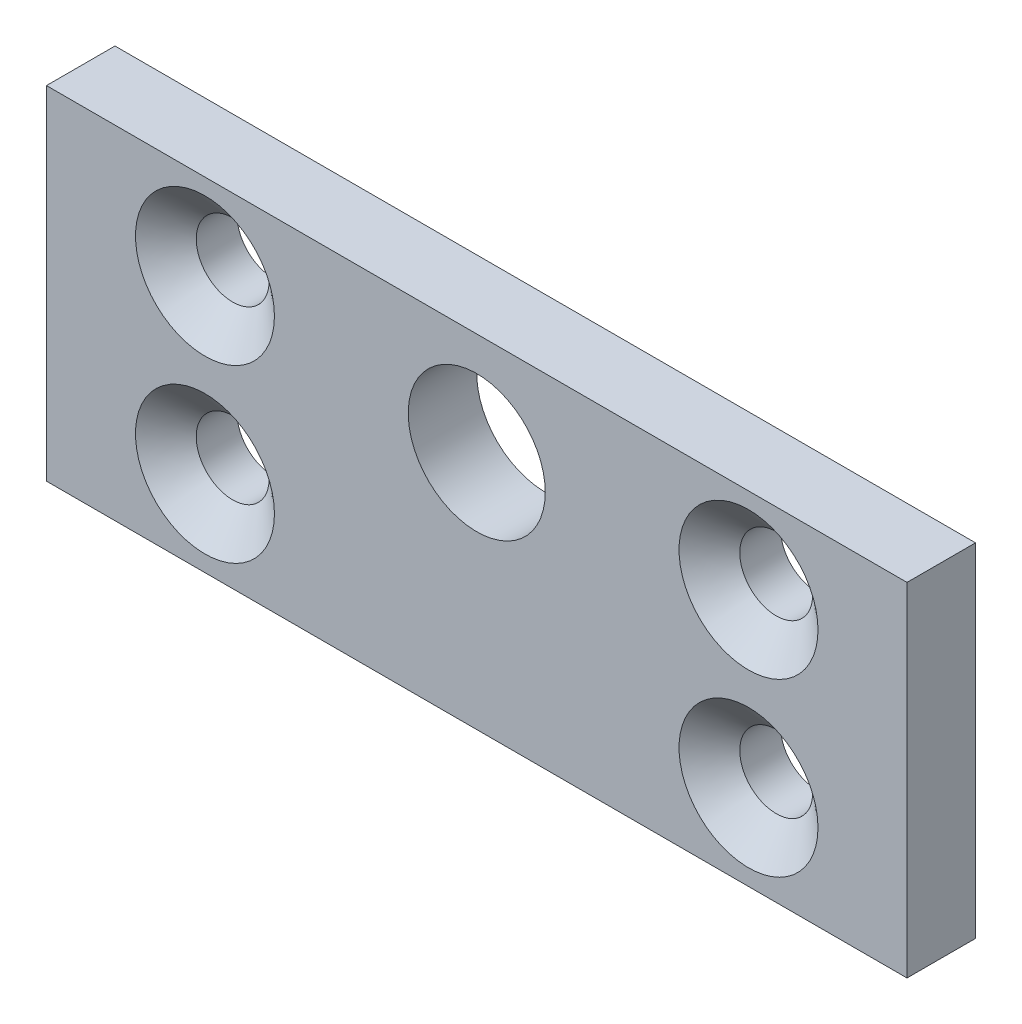
SolidWorks part; units mm, degrees
material "6061-T6 (SS)"
ref_plane "Front Plane" through (0, 0, 0) normal (0, 0, 1) x (1, 0, 0)
ref_plane "Top Plane" through (0, 0, 0) normal (0, 1, 0) x (1, 0, 0)
ref_plane "Right Plane" through (0, 0, 0) normal (1, 0, 0) x (0, 0, -1)
sketch "Sketch1" plane through (0, 0, 0) normal (0, 0, 1) x (1, 0, 0)
  line L0 (-111.125, 31.75) -> (-79.5563, 31.75) construction
  line L1 (-103.3731, 31.75) -> (-23.6269, 31.75)
  line L2 (-103.3731, 31.75) -> (-103.3731, 0)
  line L3 (-103.3731, 0) -> (-23.6269, 0)
  line L4 (-23.6269, 31.75) -> (-23.6269, 0)
  line L5 (0, 0) -> (-127, 0) construction
  line L6 (-63.5, 22.225) -> (-63.5, 0) construction
  circle A0 centre (-63.5, 22.225) radius 6.35
  point P8 (-63.5, 0)
  dimension "D2" = 12.7
  dimension "D3" = 9.525
extrude "Boss-Extrude1" add sketch "Sketch1" along normal blind 6.35 contours L3 L4 L1 L2
hole_wizard "CSK for 1/4 Flat Head Machine Screw (100)1" positions "Sketch2" profile "Sketch3" countersink size "1/4" standard "ANSI Inch" end condition through all
sketch "Sketch2" plane through (0, 0, 6.35) normal (0, 0, 1) x (1, 0, 0)
  line L0 (-63.5, 31.75) -> (-63.5, 0) construction
  line L3 (-103.3731, 15.875) -> (-34.7427, 15.875) construction
  line L5 (-29.1848, 23.8125) -> (-47.4437, 23.8125) construction
  line L6 (-88.6858, 23.8125) -> (-38.3142, 23.8125) construction
  line L7 (-88.6858, 23.8125) -> (-88.6858, 7.9375) construction
  line L8 (-88.6858, 7.9375) -> (-38.3142, 7.9375) construction
  line L9 (-38.3142, 23.8125) -> (-38.3142, 7.9375) construction
  point P0 (-88.6858, 23.8125)
  point P1 (-88.6858, 7.9375)
  point P2 (-38.3142, 7.9375)
  point P3 (-38.3142, 23.8125)
sketch "Sketch3" plane through (-88.6858, 23.8125, 6.35) normal (1, 0, 0) x (0, -1, 0)
  line L0 (0, 0) -> (0, 6.35)
  line L1 (0, 6.35) -> (3.3782, 6.35)
  line L2 (3.3782, 6.35) -> (3.3782, 2.5682)
  line L3 (3.3782, 2.5682) -> (6.4389, 0)
  line L4 (6.4389, 0) -> (0, 0)
  line L5 (-3.3782, 2.5682) -> (-6.4389, 0) construction
  line L6 (0, -6.35) -> (0, 107.95) construction
  dimension "Thru Hole Dia." = 6.7564
  dimension "Thru Hole Depth" = 6.35
  dimension "Near C'Sink Dia." = 12.8778
  dimension "Near C'Sink Angle" = 100
ref_plane "center plane" through (-63.5, 0, 0) normal (1, 0, 0) x (0, 0, -1)
equation "\"dovetail-angle\" = 55"
equation "\"dovetail-stock-width\" = 5"
equation "\"dovetail-stock-height\" = 1.25"
equation "\"dovetail-depth\" = 0.5 * \"dovetail-stock-height\""
equation "\"dovetail-throat-width\" = \"dovetail-stock-width\" - (2 * \"dovetail-depth\")"
equation "\"delta-x\" = 6"
equation "\"delta-y\" = 3"
equation "\"gib-thickness\" = 0.25"
equation "\"x-slide-length\" = \"dovetail-stock-width\" + \"delta-x\""
equation "\"y-slide-length\" = \"dovetail-stock-width\" + \"delta-y\""
equation "\"dog-point-diam\" = .149"
equation "\"dog-point-length\" = .067"
equation "\"dovetail-double-height\" = 2 * \"dovetail-depth\" + 0.5"
equation "\"acme-major-diam\" = .5"
equation "\"acme-pitch-diam\" = 0.45"
equation "\"acme-minor-diam\" = 0.4"
equation "\"acme-nut-od\" = 1.47"
equation "\"acme-nut-length\" = 1"
equation "\"acme-nut-trim-height\" = .75"
equation "\"screw-bearing-od\" = 0.5"
equation "\"screw-bearing-length\" = .25"
equation "\"screw-bearing-id\" = .375"
equation "\"end-plate-thickness\" = \"screw-bearing-length\""
equation "\"screw-add-length\" = 2 * \"end-plate-thickness\" + 1 + 0.5"
equation "\"x-screw-length\" = \"x-slide-length\" + \"screw-add-length\""
equation "\"y-screw-length\" = \"y-slide-length\" + \"screw-add-length\""
equation "\"acme-nut-mount-hole-space-horz\" = 0.82"
equation "\"acme-nut-mount-hole-space-vert\" = 0.5 * \"acme-nut-length\""
equation "\"vise-hole-center-dist\" = 6.75"
equation "\"wiper_plate_clearance\" = .03"
equation "\"D2@Sketch1\"=\"screw-bearing-od\""
equation "\"D3@Sketch1\"=\"acme-nut-trim-height\"/2"
equation "\"D1@Boss-Extrude1\"=\"screw-bearing-length\""
